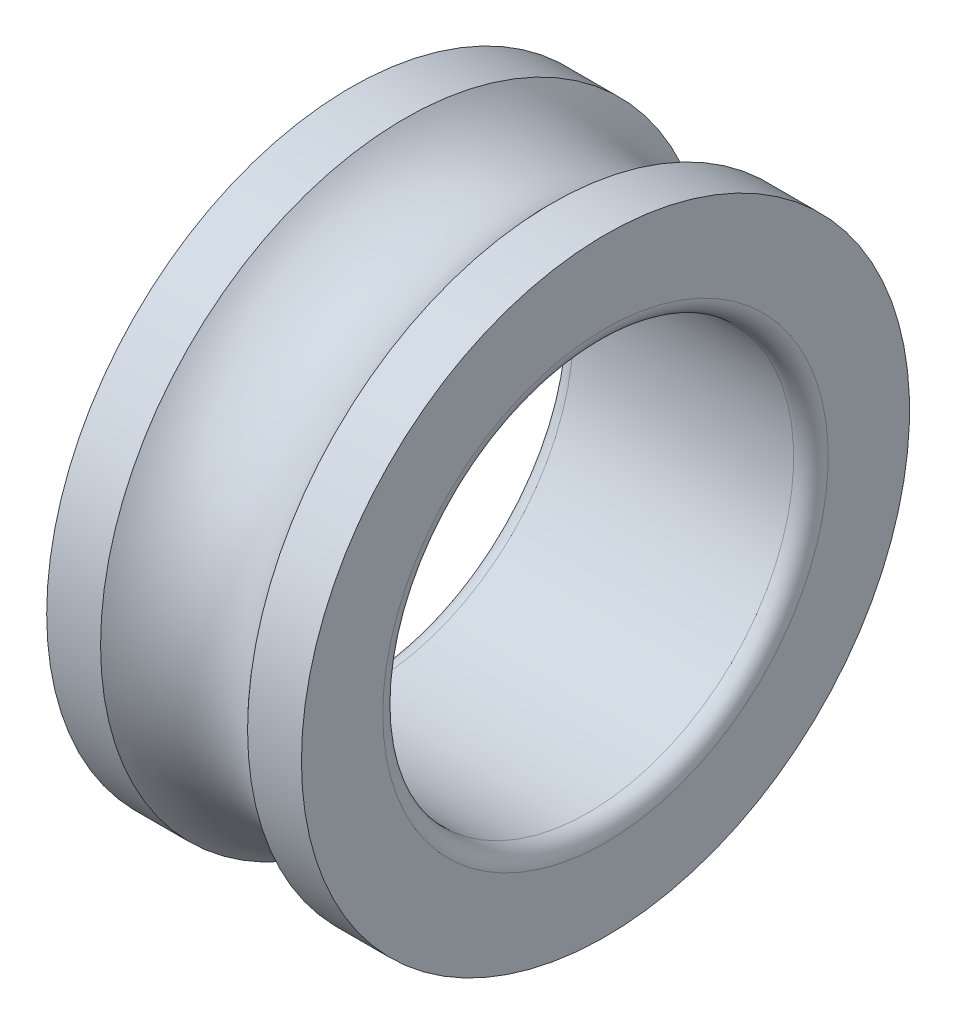
SolidWorks part; units mm, degrees
ref_plane "前基準面" through (0, 0, 0) normal (0, 0, 1) x (1, 0, 0)
ref_plane "上基準面" through (0, 0, 0) normal (0, 1, 0) x (1, 0, 0)
ref_plane "右基準面" through (0, 0, 0) normal (1, 0, 0) x (0, 0, -1)
sketch "草圖1" plane through (0, 0, 0) normal (0, 0, 1) x (1, 0, 0)
  line L0 (0, 0) -> (35.0997, 0) construction
  line L1 (0, 0) -> (0, 45) construction
  line L2 (-13.4, 25) -> (13.4, 25)
  line L3 (-15.5, 27.1) -> (-15.5, 37)
  line L4 (-15.5, 37) -> (-8.9443, 37)
  line L5 (15.5, 27.1) -> (15.5, 37)
  line L6 (8.9443, 37) -> (15.5, 37)
  arc A0 (-8.9443, 37) -> (8.9443, 37) centre (0, 45) ccw
  arc A1 (-13.4, 25) -> (-15.5, 27.1) centre (-13.4, 27.1) cw
  arc A2 (13.4, 25) -> (15.5, 27.1) centre (13.4, 27.1) ccw
  point P12 (-15.5, 25)
  point P15 (15.5, 25)
  dimension "D5" = 24
  dimension "D6" = 2.1
  dimension "D1" = 31
  dimension "D2" = 25
  dimension "D3" = 8
  dimension "D4" = 37
revolve "旋轉1" add sketch "草圖1" angle 360 about L0
